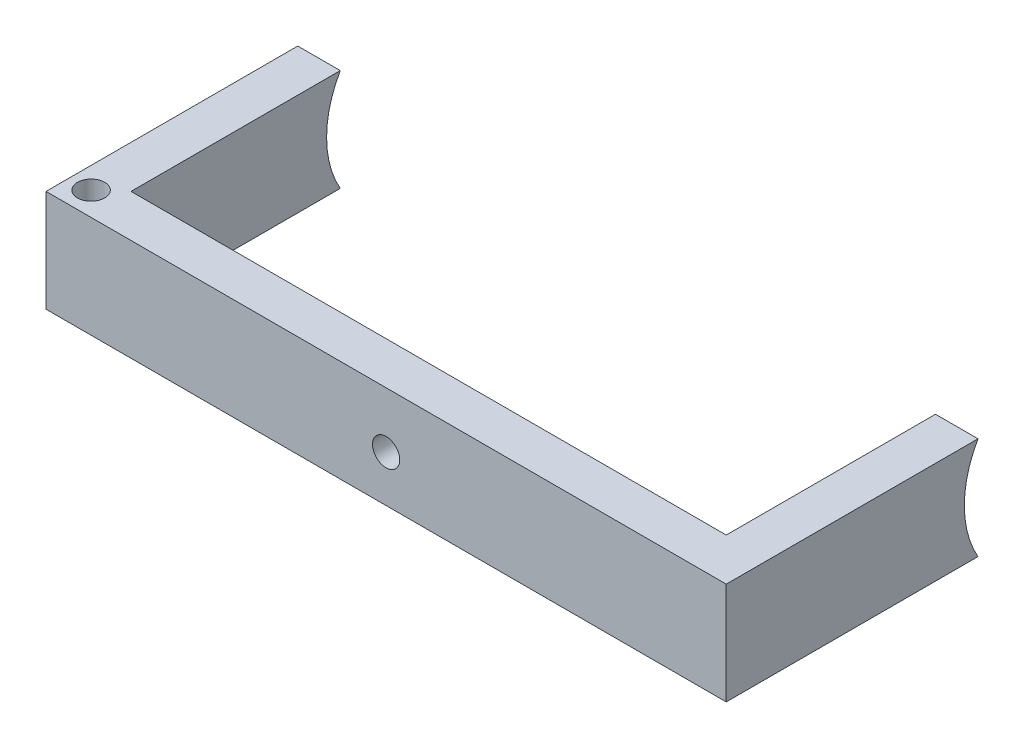
SolidWorks part; units mm, degrees
ref_plane "Front Plane" through (0, 0, 0) normal (0, 0, 1) x (1, 0, 0)
ref_plane "Top Plane" through (0, 0, 0) normal (0, 1, 0) x (1, 0, 0)
ref_plane "Right Plane" through (0, 0, 0) normal (1, 0, 0) x (0, 0, -1)
sketch "Sketch1" plane through (0, 0, 0) normal (0, 1, 0) x (1, 0, 0)
  line L1 (-100, 100) -> (100, 100)
  line L2 (-100, 100) -> (-100, -100)
  line L3 (-100, -100) -> (100, -100)
  line L4 (100, 100) -> (100, -100)
  line L5 (-100, 100) -> (100, -100) construction
  line L6 (-100, -100) -> (100, 100) construction
  point P0 (0, 0)
extrude "Boss-Extrude1" add sketch "Sketch1" along normal blind 30
sketch "Sketch4" plane through (0, 30, 0) normal (0, 1, 0) x (1, 0, 0)
  line L1 (-87.5, -87.5) -> (87.5, -87.5)
  line L2 (-87.5, -87.5) -> (-87.5, 87.5)
  line L3 (-87.5, 87.5) -> (87.5, 87.5)
  line L4 (87.5, -87.5) -> (87.5, 87.5)
  line L5 (-87.5, -87.5) -> (87.5, 87.5) construction
  line L6 (-87.5, 87.5) -> (87.5, -87.5) construction
  point P0 (0, 0)
extrude "Cut-Extrude1" cut sketch "Sketch4" against normal blind 30
sketch "Sketch7" plane through (-100, 0, 0) normal (-1, 0, 0) x (0, 0, 1)
  circle A0 centre (0, 15) radius 4
extrude "Cut-Extrude2" cut sketch "Sketch7" against normal blind 210
sketch "Sketch10" plane through (-100, 0, 0) normal (-1, 0, 0) x (0, 0, 1)
  line L0 (-8.6266, 30) -> (-8.6266, 0)
  line L1 (-100, 30) -> (100, 30) construction
  line L2 (-100, 0) -> (100, 0) construction
  line L3 (-8.6266, 0) -> (-14.6668, 0)
  line L4 (-14.6668, 0) -> (-14.6668, 30)
  line L5 (-14.6668, 30) -> (-8.6266, 30)
extrude "Boss-Extrude2" add sketch "Sketch10" along normal blind 20
sketch "Sketch11" plane through (0, 0, -8.6266) normal (0, 0, 1) x (1, 0, 0)
  line L0 (-120, 0) -> (-120, 30)
  line L1 (-120, 30) -> (-110, 30)
  line L2 (-120, 30) -> (-100, 30) construction
  line L3 (-110, 30) -> (-110, 0)
  line L4 (-120, 0) -> (-100, 0) construction
  line L5 (-110, 0) -> (-120, 0)
extrude "Boss-Extrude3" add sketch "Sketch11" along normal blind 20
sketch "Sketch12" plane through (100, 0, 0) normal (1, 0, 0) x (0, 0, -1)
  circle A0 centre (0, 15) radius 4
extrude "Cut-Extrude3" cut sketch "Sketch12" against normal blind 231
sketch "Sketch13" plane through (0, 30, 0) normal (0, 1, 0) x (1, 0, 0)
  circle A0 centre (-93.6945, -93.0455) radius 4
extrude "Cut-Extrude5" cut sketch "Sketch13" against normal blind 231
sketch "Sketch14" plane through (0, 0, 100) normal (0, 0, 1) x (1, 0, 0)
  circle A0 centre (0, 13.6147) radius 4
extrude "Cut-Extrude6" cut sketch "Sketch14" against normal blind 250.5
sketch "Sketch15" plane through (100, 0, 0) normal (1, 0, 0) x (0, 0, -1)
  circle A0 centre (0, 15) radius 30
  circle A1 centre (0, 15) radius 22
extrude "Boss-Extrude5" add sketch "Sketch15" against normal blind 201
sketch "Sketch17" plane through (100, 0, 0) normal (1, 0, 0) x (0, 0, -1)
  circle A0 centre (0.0744, 15.1008) radius 22
extrude "Cut-Extrude7" cut sketch "Sketch17" against normal blind 201
sketch "Sketch18" plane through (87.5, 0, 0) normal (-1, 0, 0) x (0, 0, 1)
  line L1 (-87.5, 0) -> (87.5, 0)
  line L2 (-87.5, 0) -> (-87.5, 30)
  line L3 (-87.5, 30) -> (87.5, 30)
  line L4 (87.5, 0) -> (87.5, 30)
sketch "Sketch21" plane through (0, 0, -14.6668) normal (0, 0, -1) x (-1, 0, 0)
  line L0 (120, 30) -> (120, 0) construction
  line L1 (120, 1.1441) -> (110.5, 1.1441)
  line L2 (120, 1.1441) -> (120, 30)
  line L3 (120, 30) -> (110.5, 30)
  line L4 (110.5, 1.1441) -> (110.5, 30)
  line L5 (120, 30) -> (101, 30) construction
extrude "Boss-Extrude6" add sketch "Sketch21" along normal blind 26
sketch "Sketch22" plane through (0, 30, 0) normal (0, 1, 0) x (1, 0, 0)
  line L1 (-110.5, 14.6668) -> (-101, 14.6668)
  line L2 (-110.5, 14.6668) -> (-110.5, 8.6266)
  line L3 (-110.5, 8.6266) -> (-101, 8.6266)
  line L4 (-101, 14.6668) -> (-101, 8.6266)
extrude "Cut-Extrude10" cut sketch "Sketch22" against normal blind 49
sketch "Sketch23" plane through (-110.5, 0, 0) normal (1, 0, 0) x (0, 0, -1)
  line L0 (40.6668, 1.1441) -> (14.6668, 1.1441) construction
  line L1 (40.6668, 30) -> (30.6579, 30)
  line L2 (40.6668, 30) -> (40.6668, 1.1441)
  line L3 (40.6668, 1.1441) -> (30.6579, 1.1441)
  line L4 (30.6579, 30) -> (30.6579, 1.1441)
extrude "Boss-Extrude7" add sketch "Sketch23" along normal blind 21
sketch "Sketch24" plane through (0, 0, -14.6668) normal (0, 0, -1) x (-1, 0, 0)
  line L1 (120, 0) -> (110.5, 0)
  line L2 (120, 0) -> (120, 1.1441)
  line L3 (120, 1.1441) -> (110.5, 1.1441)
  line L4 (110.5, 0) -> (110.5, 1.1441)
extrude "Cut-Extrude11" cut sketch "Sketch24" against normal blind 27
sketch "Sketch26" plane through (0, 0, 0) normal (0, -1, 0) x (1, 0, 0)
  line L1 (-110.5, -8.6266) -> (-109.9986, -8.6266)
  line L2 (-110.5, -8.6266) -> (-110.5, 12.267)
  line L3 (-110.5, 12.267) -> (-109.9986, 12.267)
  line L4 (-109.9986, -8.6266) -> (-109.9986, 12.267)
extrude "Cut-Extrude12" cut sketch "Sketch26" against normal blind 35
sketch "Sketch27" plane through (-87.5, 0, 0) normal (1, 0, 0) x (0, 0, -1)
  circle A0 centre (-31.9164, 15.3761) radius 49.1928
extrude "Cut-Extrude13" cut sketch "Sketch27" along normal blind 175
sketch "Sketch28" plane through (-87.5, 0, 0) normal (1, 0, 0) x (0, 0, -1)
  circle A0 centre (37.7624, 15.4944) radius 41.209
extrude "Cut-Extrude14" cut sketch "Sketch28" along normal blind 175
sketch "Sketch29" plane through (100, 0, 0) normal (1, 0, 0) x (0, 0, -1)
  circle A0 centre (0, 15) radius 30
sketch "Sketch30" plane through (87.5, 0, 0) normal (-1, 0, 0) x (0, 0, 1)
  circle A0 centre (-13.582, -10.1635) radius 19.2473
sketch "Sketch31" plane through (-87.5, 0, 0) normal (1, 0, 0) x (0, 0, -1)
  circle A0 centre (-2.2061, -10.8507) radius 25.6712
extrude "Cut-Extrude15" cut sketch "Sketch31" along normal blind 175
sketch "Sketch32" plane through (100, 0, 0) normal (1, 0, 0) x (0, 0, -1)
  line L0 (87.5, 0) -> (-87.5, 0) construction
  arc A0 (-25.9808, 30) -> (-25.9808, 0) centre (0, 15) ccw
extrude "Cut-Extrude16" cut sketch "Sketch32" against normal blind 220 and the other way through all
sketch "Sketch33" plane through (100, 0, 0) normal (1, 0, 0) x (0, 0, -1)
  circle A0 centre (0, 15) radius 30
